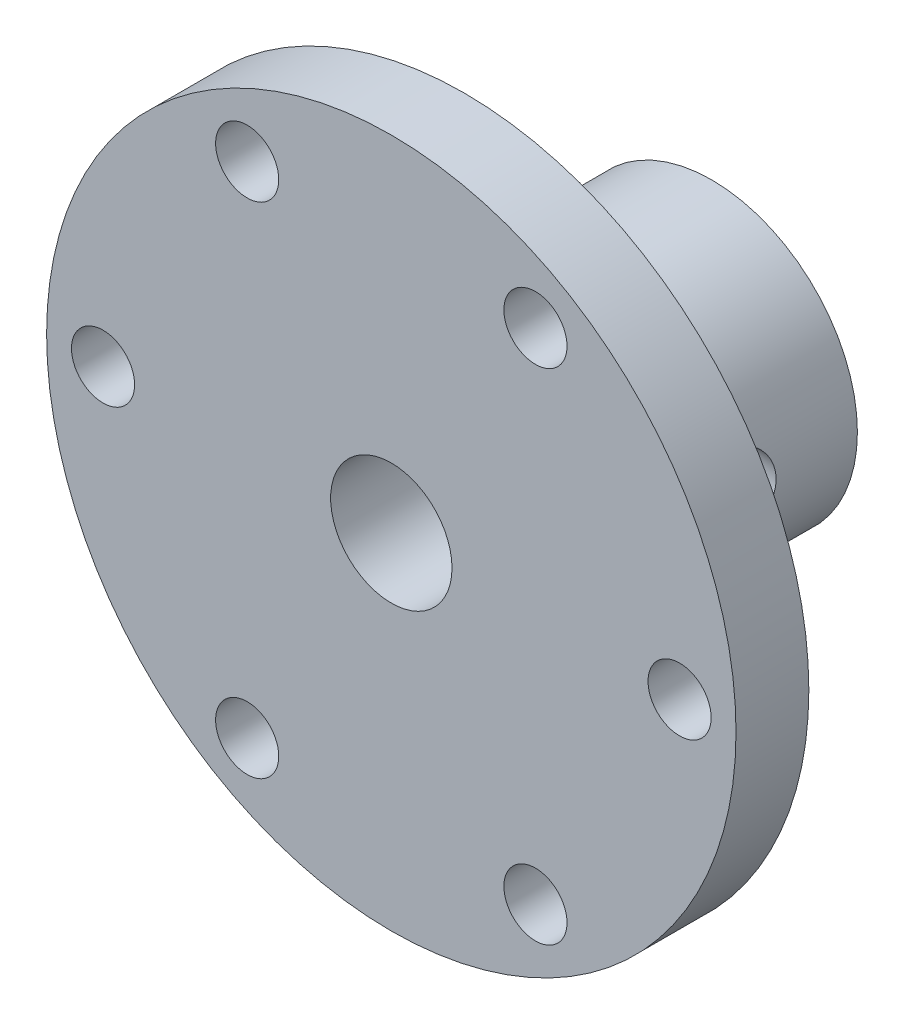
SolidWorks part; units mm, degrees
material "5052-H32"
ref_plane "正面" through (0, 0, 0) normal (0, 0, 1) x (1, 0, 0)
ref_plane "平面" through (0, 0, 0) normal (0, 1, 0) x (1, 0, 0)
ref_plane "右側面" through (0, 0, 0) normal (1, 0, 0) x (0, 0, -1)
sketch "ｽｹｯﾁ1" plane through (0, 0, 0) normal (0, 0, 1) x (1, 0, 0)
  circle A0 centre (0, 0) radius 28.4
  dimension "D1" = 56.8
extrude "ﾎﾞｽ - 押し出し1" add sketch "ｽｹｯﾁ1" along normal blind 6
sketch "ｽｹｯﾁ2" plane through (0, 0, 0) normal (0, 0, 1) x (1, 0, 0)
  circle A0 centre (0, 0) radius 12
  dimension "D1" = 24
extrude "ﾎﾞｽ - 押し出し2" add sketch "ｽｹｯﾁ2" against normal offset from surface (20.4 mm away) 26.4 up to face at (28.4, 0, 6)
sketch "ｽｹｯﾁ3" plane through (0, 0, 0) normal (0, 0, 1) x (1, 0, 0)
  circle A0 centre (0, 0) radius 5
  dimension "D1" = 10
extrude "ｶｯﾄ - 押し出し1" cut sketch "ｽｹｯﾁ3" against normal through all both and the other way through all
hole_wizard "M6 すきま穴1" positions "ｽｹｯﾁ4" profile "ｽｹｯﾁ5" hole size "M6" standard "JIS"
sketch "ｽｹｯﾁ4" plane through (0, 0, 0) normal (1, 0, 0) x (0, 0, -1)
  line L0 (20.4, -12) -> (20.4, 12) construction
  point P0 (10.2, 0)
  point P5 (0, 0)
  dimension "D1" = 10.2
sketch "ｽｹｯﾁ5" plane through (0, 0, -10.2) normal (0, 1, 0) x (0, 0, 1)
  line L0 (0, 0) -> (0, 12)
  line L1 (0, 12) -> (3.5, 12)
  line L2 (3.5, 12) -> (3.5, 0)
  line L5 (3.5, 0) -> (0, 0)
  line L11 (0, -6.35) -> (0, 107.95) construction
  dimension "通し穴の直径" = 7
  dimension "通し穴の深さ" = 12
sketch "ｽｹｯﾁ7" plane through (0, 0, 0) normal (0, 0, 1) x (1, 0, 0)
  circle A0 centre (0, 0) radius 23.75 construction
  circle A1 centre (23.75, 0) radius 2.6
  point P5 (23.75, 0)
  point P6 (0, 0)
  dimension "D1" = 47.5
  dimension "D2" = 5.2
extrude "ｶｯﾄ - 押し出し2" cut sketch "ｽｹｯﾁ7" against normal through all both and the other way through all
pattern_circular "円形ﾊﾟﾀｰﾝ1" count 6 over 360 about axis through (0, 0, 0) along (0, 0, 1) of "ｶｯﾄ - 押し出し2"
